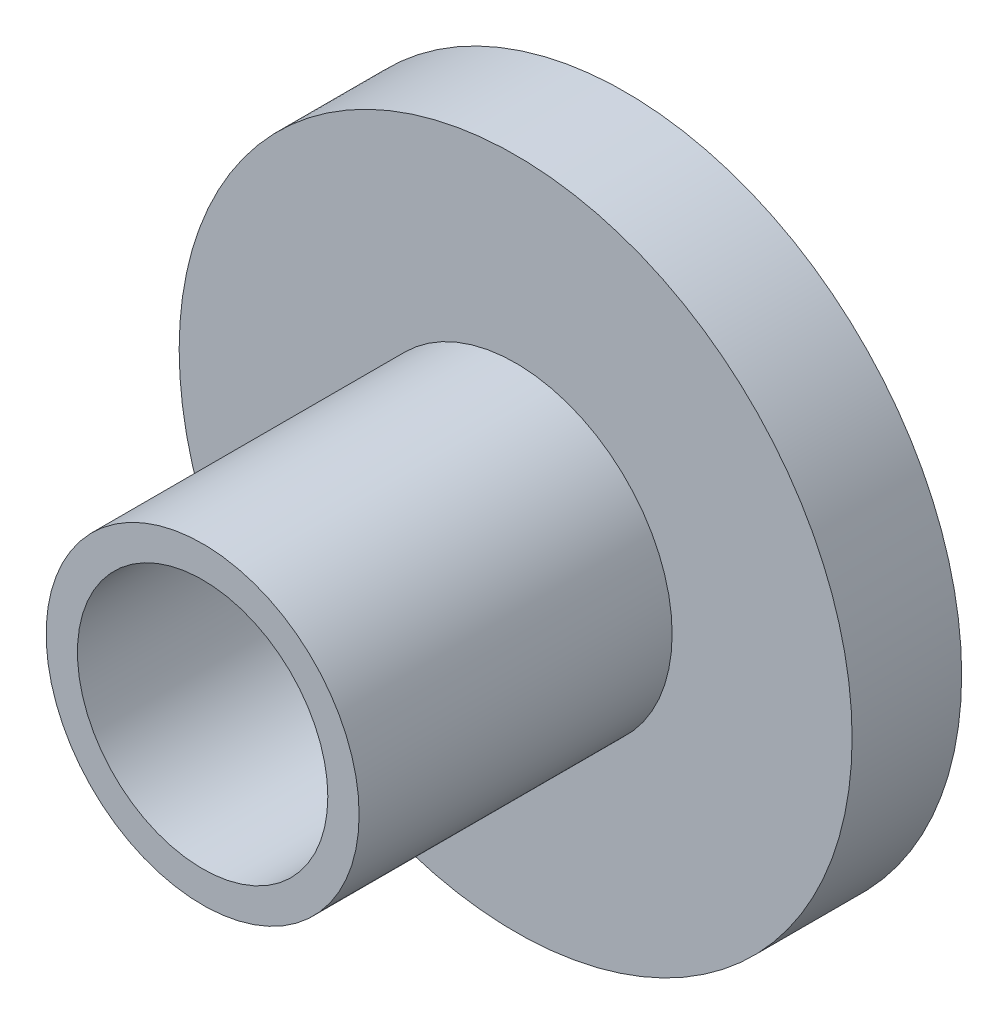
SolidWorks part; units mm, degrees
ref_plane "Front Plane" through (0, 0, 0) normal (0, 0, 1) x (1, 0, 0)
ref_plane "Top Plane" through (0, 0, 0) normal (0, 1, 0) x (1, 0, 0)
ref_plane "Right Plane" through (0, 0, 0) normal (1, 0, 0) x (0, 0, -1)
sketch "Sketch1" plane through (0, 0, 0) normal (0, 0, 1) x (1, 0, 0)
  circle A0 centre (0, 0) radius 10.75
  dimension "D1" = 21.5
extrude "Boss-Extrude1" add sketch "Sketch1" along normal blind 3.5
sketch "Sketch2" plane through (0, 0, 3.5) normal (0, 0, 1) x (1, 0, 0)
  circle A0 centre (0, 0) radius 5
  dimension "D1" = 10
extrude "Boss-Extrude2" add sketch "Sketch2" along normal blind 10
sketch "Sketch3" plane through (0, 0, 13.5) normal (0, 0, 1) x (1, 0, 0)
  circle A0 centre (0, 0) radius 4
  dimension "D1" = 8
extrude "Cut-Extrude1" cut sketch "Sketch3" against normal up to next
